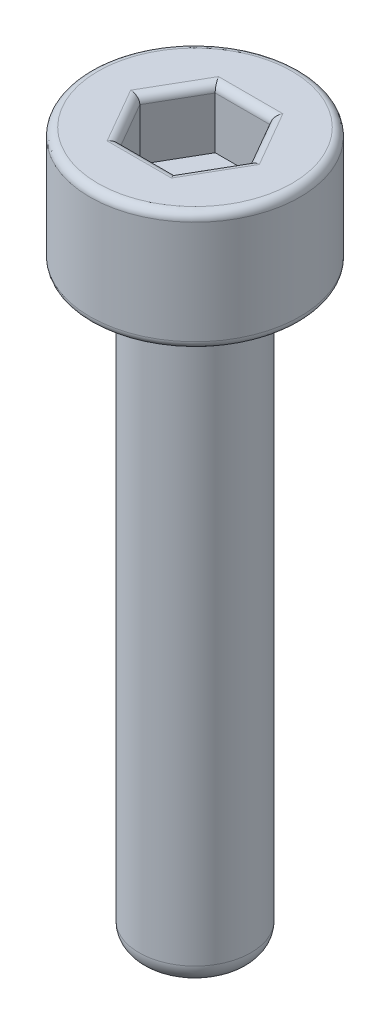
SolidWorks part; units mm, degrees
ref_plane "Front Plane" through (0, 0, 0) normal (0, 0, 1) x (1, 0, 0)
ref_plane "Top Plane" through (0, 0, 0) normal (0, 1, 0) x (1, 0, 0)
ref_plane "Right Plane" through (0, 0, 0) normal (1, 0, 0) x (0, 0, -1)
sketch "Sketch1" plane through (0, 0, 0) normal (0, 1, 0) x (1, 0, 0)
  circle A0 centre (0, 0) radius 2.64
  dimension "D1" = 5.28
extrude "Boss-Extrude1" add sketch "Sketch1" along normal blind 3
sketch "Sketch2" plane through (0, 0, 0) normal (0, -1, 0) x (1, 0, 0)
  circle A0 centre (0, 0) radius 1.405
  dimension "D1" = 2.81
extrude "Boss-Extrude2" add sketch "Sketch2" along normal blind 14.76
fillet "Fillet1" radius 0.2 2 edges at (0, 3, 2.64) (0, 0, 2.64)
sketch "Sketch3" plane through (0, 3, 0) normal (0, 1, 0) x (1, 0, 0)
  line L1 (1.3856, 0) -> (0.6928, 1.2)
  line L2 (0.6928, 1.2) -> (-0.6928, 1.2)
  line L3 (-0.6928, 1.2) -> (-1.3856, 0)
  line L4 (-1.3856, 0) -> (-0.6928, -1.2)
  line L5 (-0.6928, -1.2) -> (0.6928, -1.2)
  line L6 (0.6928, -1.2) -> (1.3856, 0)
  circle A0 centre (0, 0) radius 1.2 construction
  dimension "D1" = 2.4
extrude "Cut-Extrude1" cut sketch "Sketch3" against normal blind 1.5
fillet "Fillet2" radius 0.2 6 edges at (1.0392, 3, -0.6) (0, 3, -1.2) (-1.0392, 3, -0.6) (-1.0392, 3, 0.6) (0, 3, 1.2) (1.0392, 3, 0.6)
fillet "Fillet3" radius 0.5 1 edges at (0, -14.76, -1.405)
